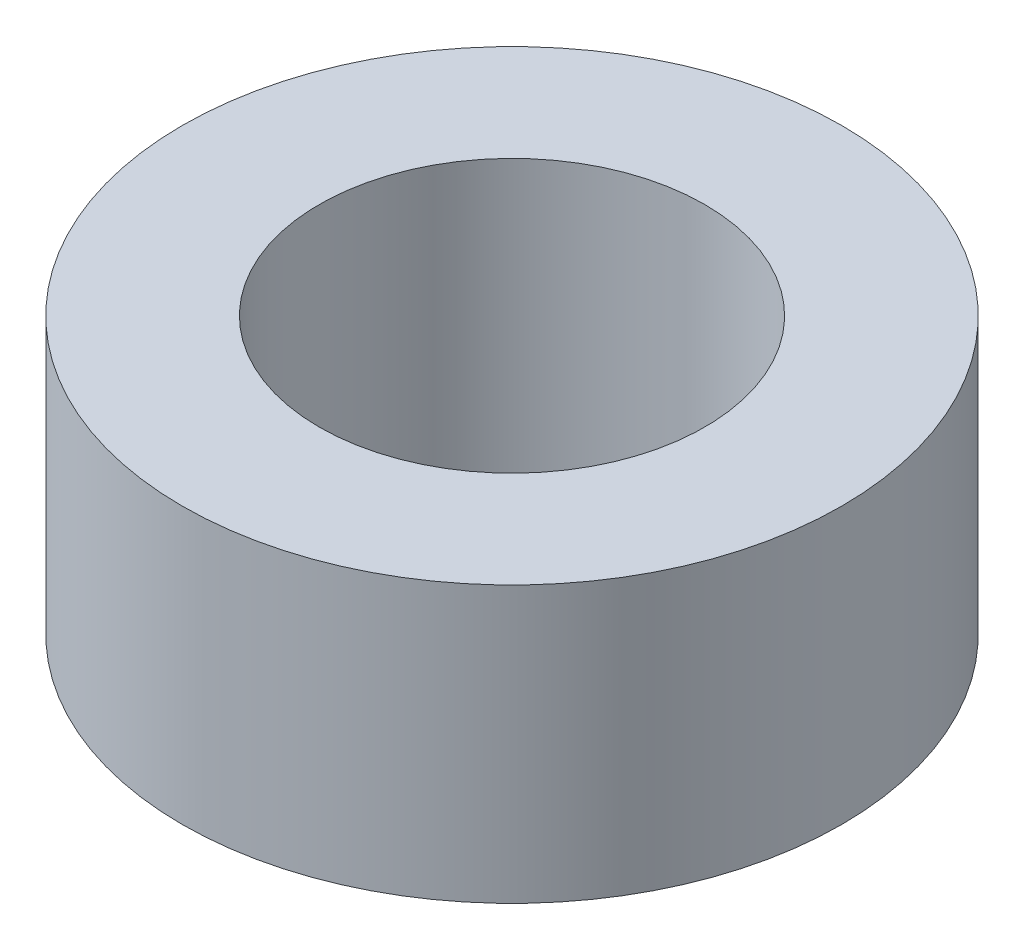
SolidWorks part; units mm, degrees
ref_plane "Front Plane" through (0, 0, 0) normal (0, 0, 1) x (1, 0, 0)
ref_plane "Top Plane" through (0, 0, 0) normal (0, 1, 0) x (1, 0, 0)
ref_plane "Right Plane" through (0, 0, 0) normal (1, 0, 0) x (0, 0, -1)
sketch "Sketch1" plane through (0, 0, 0) normal (0, 1, 0) x (1, 0, 0)
  circle A0 centre (0, 0) radius 1.608
  circle A1 centre (0, 0) radius 2.75
  dimension "D1" = 3.216
  dimension "D2" = 5.5
extrude "Boss-Extrude1" add sketch "Sketch1" along normal blind 2.3
